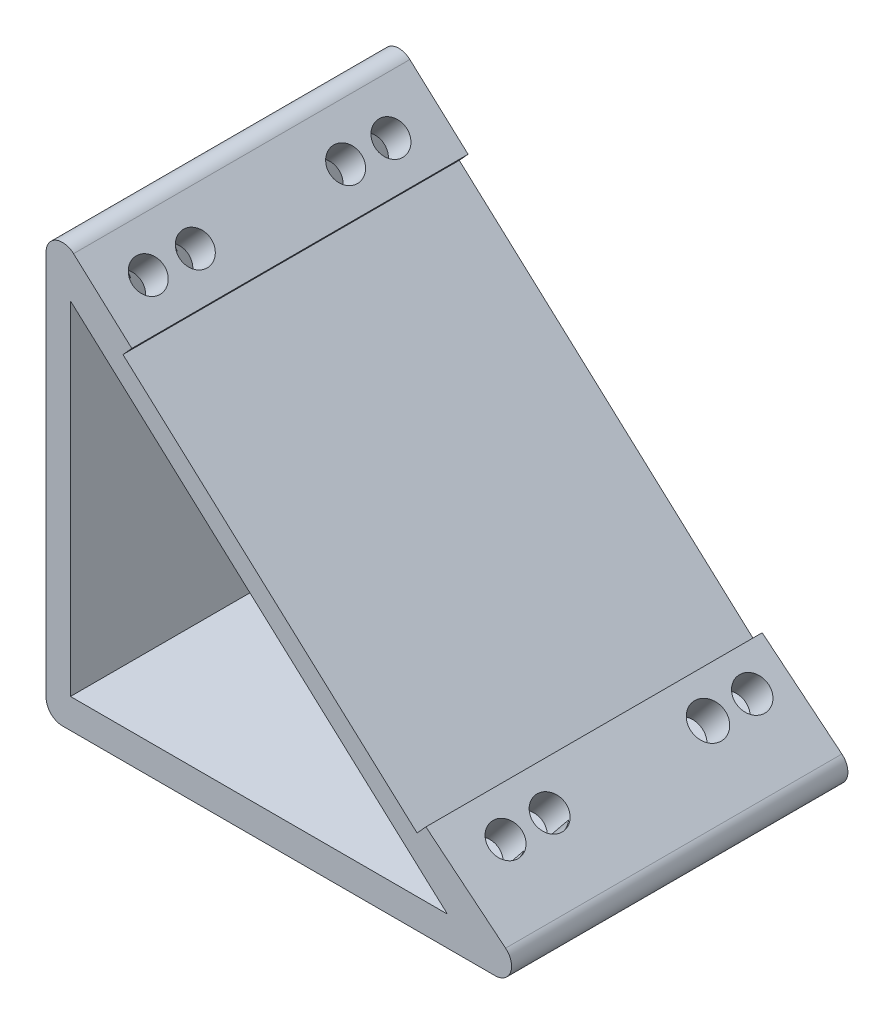
SolidWorks part; units mm, degrees
ref_plane "Front Plane" through (0, 0, 0) normal (0, 0, 1) x (1, 0, 0)
ref_plane "Top Plane" through (0, 0, 0) normal (0, 1, 0) x (1, 0, 0)
ref_plane "Right Plane" through (0, 0, 0) normal (1, 0, 0) x (0, 0, -1)
sketch "Sketch1" plane through (0, 0, 0) normal (0, 0, 1) x (1, 0, 0)
  line L0 (-26.9623, 42.1083) -> (-26.9623, -25.9341)
  line L1 (-26.9623, -25.9341) -> (49.6838, -25.9341)
  line L3 (-23.1921, -21.3642) -> (-23.1921, 31.6844)
  line L4 (-23.1921, 31.6844) -> (35.1777, -21.3642)
  line L5 (35.1777, -21.3642) -> (-23.1921, -21.3642)
  line L6 (-26.9623, 42.1083) -> (-13.6981, 30.0533)
  line L7 (-13.6981, 30.0533) -> (-15.0637, 28.5508)
  line L8 (-15.0637, 28.5508) -> (30.4748, -12.8361)
  line L9 (30.4748, -12.8361) -> (31.8403, -11.3336)
  line L10 (31.8403, -11.3336) -> (49.6838, -25.9341)
extrude "Boss-Extrude2" add sketch "Sketch1" along normal blind 52.07
fillet "Fillet1" radius 2.54 2 edges at (49.6838, -25.9341, 26.035) (-26.9623, 42.1083, 26.035)
fillet "Fillet2" radius 2.54 1 edges at (-26.9623, -25.9341, 26.035)
sketch "Sketch2" plane through (8.7619, 9.6408, 0) normal (0.6726, 0.74, 0) x (0.74, -0.6726, 0)
  circle A0 centre (-36.4107, -45.0398) radius 2.4879
  circle A1 centre (-36.3429, -37.7948) radius 2.4879
  circle A2 centre (-36.1139, -14.6958) radius 2.4879
  circle A3 centre (-36.1139, -7.6775) radius 2.4879
  circle A4 centre (38.1975, -45.0038) radius 2.4879
  circle A5 centre (38.2653, -37.7588) radius 2.4879
  circle A6 centre (38.4943, -14.6598) radius 2.4879
  circle A7 centre (38.4943, -7.6415) radius 2.4879
  point P8 (-36.1139, -7.6775)
extrude "Cut-Extrude1" cut sketch "Sketch2" against normal blind 6.35
sketch "Sketch3" plane through (7.2142, 8.8166, 0) normal (0.6333, 0.7739, 0) x (0.7739, -0.6333, 0)
  circle A2 centre (36.8242, -5.7467) radius 2.5115
  circle A3 centre (36.9339, -12.6593) radius 2.5115
  circle A4 centre (37.2976, -37.1512) radius 2.5115
  circle A5 centre (37.4073, -44.0639) radius 2.5115
extrude "Cut-Extrude2" cut sketch "Sketch3" against normal blind 6.35 contours A4 | A5
sketch "Sketch4" plane through (7.2142, 8.8166, 0) normal (0.6333, 0.7739, 0) x (0.7739, -0.6333, 0)
  circle A0 centre (37.1005, -5.6306) radius 2.5355
  circle A1 centre (37.2325, -12.5822) radius 2.6636
extrude "Cut-Extrude3" cut sketch "Sketch4" against normal blind 6.35 contours A1 | A0
